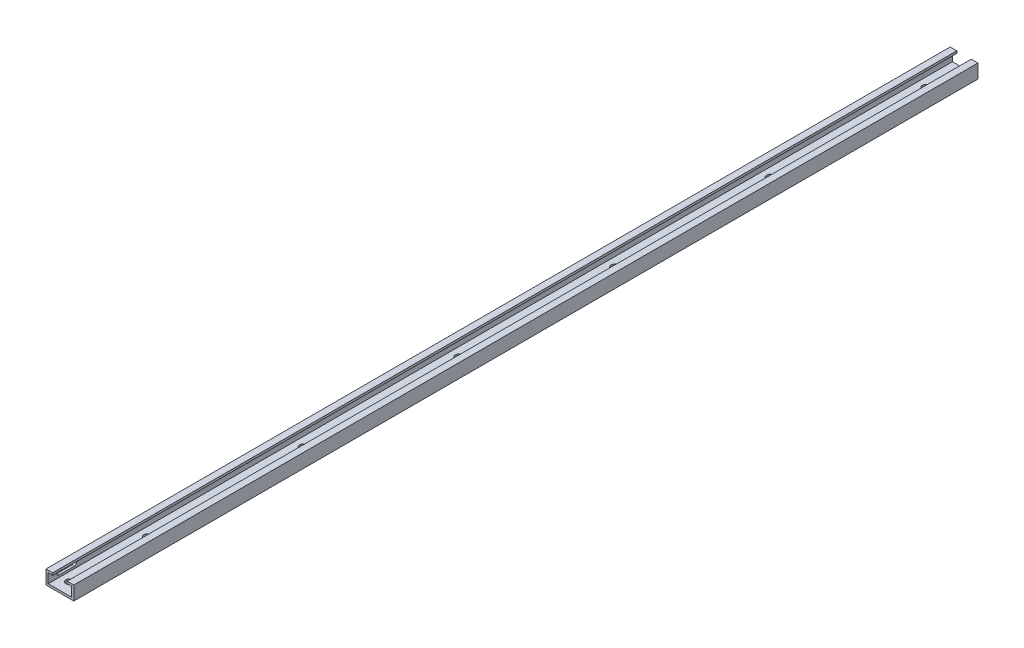
SolidWorks part; units mm, degrees
ref_plane "Plan de face" through (0, 0, 0) normal (0, 0, 1) x (1, 0, 0)
ref_plane "Plan de dessus" through (0, 0, 0) normal (0, 1, 0) x (1, 0, 0)
ref_plane "Plan de droite" through (0, 0, 0) normal (1, 0, 0) x (0, 0, -1)
sketch "Esquisse1" plane through (0, 0, 0) normal (0, 0, 1) x (1, 0, 0)
  line L0 (-6.5, 12.5) -> (-12.5, 12.5)
  line L1 (-12.5, 12.5) -> (-12.5, 0)
  line L2 (-12.5, 0) -> (12.5, 0)
  line L3 (12.5, 0) -> (12.5, 12.5)
  line L4 (12.5, 12.5) -> (6.5, 12.5)
  line L5 (0, 8.7838) -> (0, -4.9459) construction
  line L6 (-6.5, 10.5) -> (-10.5, 10.5)
  line L7 (-10.5, 10.5) -> (-10.5, 2)
  line L8 (-10.5, 2) -> (10.5, 2)
  line L9 (10.5, 2) -> (10.5, 10.5)
  line L10 (10.5, 10.5) -> (6.5, 10.5)
  line L11 (-6.5, 12.5) -> (-6.5, 10.5)
  line L12 (6.5, 12.5) -> (6.5, 10.5)
  dimension "D1" = 13
  dimension "D2" = 25
  dimension "D4" = 2
  dimension "D3" = 12.5
extrude "Boss.-Extru.1" add sketch "Esquisse1" along normal blind 813
hole_wizard "Dégagement M61" positions "Esquisse3" profile "Esquisse2" hole size "M6" standard "JIS" end condition through all
sketch "Esquisse3" plane through (0, 0, 0) normal (0, -1, 0) x (-1, 0, 0)
  point P0 (2.4063, -801.8069)
sketch "Esquisse2" plane through (-2.4063, 0, 801.8069) normal (1, 0, 0) x (0, 0, -1)
  line L0 (0, 0) -> (0, 12.5)
  line L1 (0, 12.5) -> (3.3, 12.5)
  line L2 (3.3, 12.5) -> (3.3, 0)
  line L5 (3.3, 0) -> (0, 0)
  line L11 (0, -6.35) -> (0, 107.95) construction
  dimension "Diamètre du perçage jusqu'au prochain" = 6.6
  dimension "Profondeur du perçage jusqu'au prochain" = 12.5
pattern_linear "Répétition linéaire1" count 12 spacing 70 along (0, 0, -1) skipping (2, 0), (4, 0), (6, 0), (8, 0), (10, 0) of "Dégagement M61"
sketch "Sketch1" plane through (-12.5, 0, 0) normal (1, 0, 0) x (0, 0, -1)
  line L0 (-803, 6.4491) -> (-789.8371, 6.4491) construction
  line L1 (-803, 8.9491) -> (-789.8371, 8.9491)
  line L2 (-803, 3.9491) -> (-789.8371, 3.9491)
  line L3 (-813, 0) -> (-813, 12.5) construction
  arc A0 (-803, 8.9491) -> (-803, 3.9491) centre (-803, 6.4491) ccw
  arc A1 (-789.8371, 3.9491) -> (-789.8371, 8.9491) centre (-789.8371, 6.4491) ccw
  point P2 (-796.4186, 6.4491)
  dimension "D1" = 10
  dimension "D2" = 5
extrude "Cut-Extrude1" cut sketch "Sketch1" along normal blind 5
